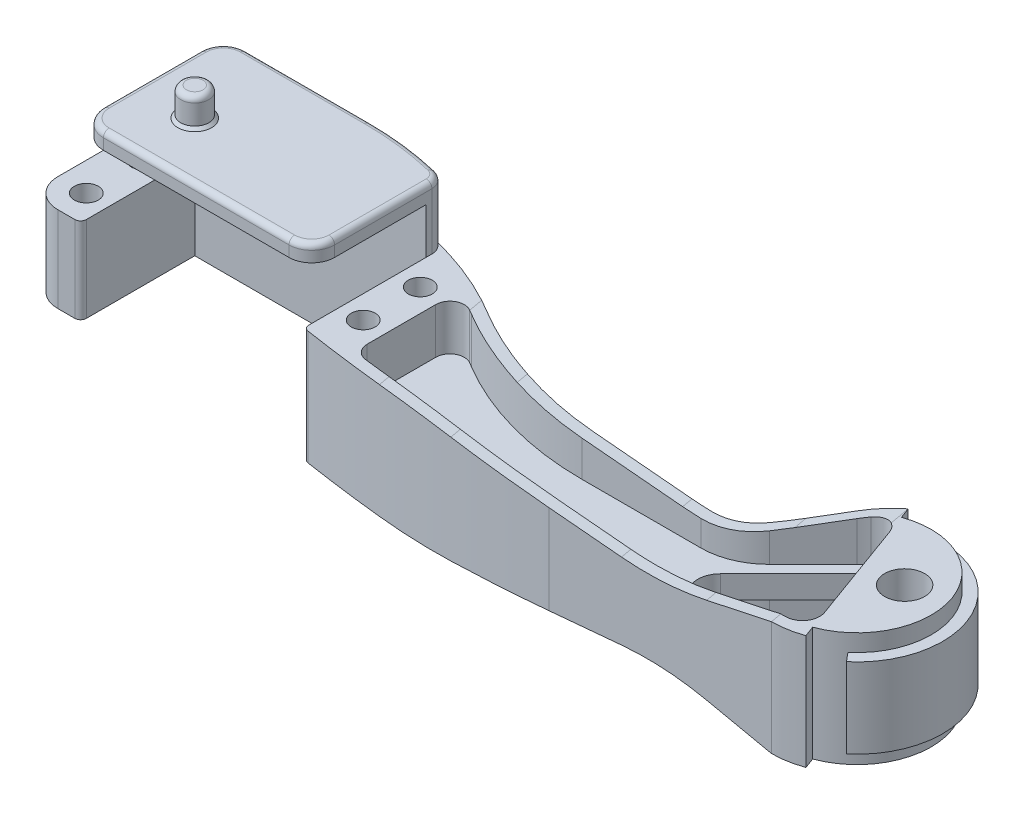
SolidWorks part; units mm, degrees
ref_plane "Alzado" through (0, 0, 0) normal (0, 0, 1) x (1, 0, 0)
ref_plane "Planta" through (0, 0, 0) normal (0, 1, 0) x (1, 0, 0)
ref_plane "Vista lateral" through (0, 0, 0) normal (1, 0, 0) x (0, 0, -1)
sketch "Croquis1" plane through (0, 0, 0) normal (0, 1, 0) x (1, 0, 0)
  line L0 (-65, 15) -> (-40.2965, 15)
  line L1 (-75, -15) -> (75, -15) construction
  line L2 (-75, -15) -> (-75, 15) construction
  line L3 (-75, 15) -> (75, 15) construction
  line L4 (75, -15) -> (75, 15) construction
  line L5 (-75, -15) -> (75, 15) construction
  line L6 (-75, 15) -> (75, -15) construction
  line L7 (13.7868, 0) -> (34.6447, 0)
  line L8 (41.7157, 2.9289) -> (49.3934, 10.6066)
  line L9 (60, -15) -> (21, -15)
  line L10 (-25.5, -10.5178) -> (-25.5, 10)
  line L11 (-25.5, 10) -> (-66, 10)
  line L12 (-66, 10) -> (-66, -9)
  line L13 (-67, -10) -> (-70, -10)
  line L14 (-75, -5) -> (-75, 5)
  line L18 (57.4617, 6.9739) -> (62.5383, -6.9739)
  line L19 (59.7192, -11) -> (43.109, -11)
  line L20 (40.2805, -4.1716) -> (52.5213, 8.0692)
  line L21 (60, 0) -> (60, 15) construction
  line L22 (57.4617, 6.9739) -> (54.8697, 14.0954) construction
  line L23 (62.5383, -6.9739) -> (65.1303, -14.0954) construction
  line L24 (60, 0) -> (69.6418, -11.4907) construction
  line L25 (54.8697, 14.0954) -> (55.5537, 12.216)
  line L26 (60, 15) -> (60, 13)
  line L27 (65.1303, -14.0954) -> (64.4463, -12.216)
  line L28 (69.6418, -11.4907) -> (68.3562, -9.9586)
  line L29 (60, 0) -> (66.108, 2.2231) construction
  arc A0 (-40.2965, 15) -> (-11.9671, 7.1429) centre (-40.2965, -40) cw
  arc A1 (-11.9671, 7.1429) -> (13.7868, 0) centre (13.7868, 50) ccw
  arc A3 (49.3934, 10.6066) -> (54.8697, 14.0954) centre (60, 0) cw
  arc A4 (21, -15) -> (-24.6522, -11.5061) centre (21, 285) cw
  arc A5 (-24.6522, -11.5061) -> (-25.5, -10.5178) centre (-24.5, -10.5178) cw
  arc A6 (-66, -9) -> (-67, -10) centre (-67, -9) cw
  arc A7 (-75, 5) -> (-65, 15) centre (-65, 5) cw
  arc A8 (-75, -5) -> (-70, -10) centre (-70, -5) ccw
  arc A9 (41.7157, 2.9289) -> (34.6447, 0) centre (34.6447, 10) cw
  arc A10 (43.109, -11) -> (40.2805, -4.1716) centre (43.109, -7) cw
  arc A11 (57.4617, 6.9739) -> (52.5213, 8.0692) centre (54.6426, 5.9479) ccw
  arc A12 (62.5383, -6.9739) -> (59.7192, -11) centre (59.7192, -8) cw
  arc A14 (65.1303, -14.0954) -> (60, -15) centre (60, 0) cw
  arc A15 (60, 15) -> (69.6418, -11.4907) centre (60, 0) cw
  arc A16 (64.4463, -12.216) -> (68.3562, -9.9586) centre (60, 0) ccw
  arc A17 (60, 13) -> (55.5537, 12.216) centre (60, 0) ccw
  circle A18 centre (66.108, 2.2231) radius 3.5
  point P0 (0, 0)
  point P33 (-75, -10)
  point P36 (60, 0)
  point P37 (60, 0)
  point P38 (60, 0)
  point P51 (38.7868, 0)
  dimension "D3" = 10
  dimension "D4" = 5
  dimension "D6" = 1
  dimension "D10" = 55
  dimension "D11" = 50
  dimension "D13" = 10
  dimension "D14" = 15
  dimension "D16" = 300
  dimension "D17" = 1
  dimension "D21" = 4
  dimension "D22" = 3
  dimension "D23" = 3
  dimension "D24" = 13
  dimension "D26" = 6.5
  dimension "D27" = 7
  dimension "D1" = 150
  dimension "D2" = 30
  dimension "D5" = 10
  dimension "D7" = 19
  dimension "D8" = 3
  dimension "D9" = 40.5
  dimension "D12" = 25
  dimension "D15" = 39
  dimension "D18" = 135
  dimension "D19" = 20
  dimension "D20" = 4
  dimension "D25" = 20
extrude "Saliente-Extruir1" add sketch "Croquis1" along normal mid plane 4
sketch "Croquis2" plane through (0, 0, 0) normal (0, 1, 0) x (1, 0, 0)
  line L0 (54.8697, 14.0954) -> (55.5537, 12.216) construction
  line L1 (41.7157, 2.9289) -> (49.3934, 10.6066) construction
  line L2 (13.7868, 0) -> (34.6447, 0) construction
  line L3 (60, -15) -> (21, -15) construction
  line L4 (-65, 15) -> (-40.2965, 15) construction
  line L5 (-25.5, -10.5178) -> (-25.5, 10) construction
  line L6 (-25.5, 10) -> (-66, 10) construction
  line L7 (-66, 10) -> (-66, -9) construction
  line L8 (-67, -10) -> (-70, -10) construction
  line L9 (-75, -5) -> (-75, 5) construction
  line L10 (54.8697, 14.0954) -> (55.5537, 12.216)
  line L11 (41.7157, 2.9289) -> (49.3934, 10.6066)
  line L12 (13.7868, 0) -> (34.6447, 0)
  line L13 (60, -15) -> (21, -15)
  line L14 (-65, 15) -> (-40.2965, 15)
  line L15 (-25.5, -10.5178) -> (-25.5, 10)
  line L16 (-25.5, 10) -> (-66, 10)
  line L17 (-66, 10) -> (-66, -9)
  line L18 (-67, -10) -> (-70, -10)
  line L19 (-75, -5) -> (-75, 5)
  line L20 (65.1303, -14.0954) -> (64.4463, -12.216) construction
  line L21 (65.1303, -14.0954) -> (64.4463, -12.216)
  line L22 (13.7868, -2) -> (34.6447, -2)
  line L23 (43.1299, 1.5147) -> (50.8076, 9.1924)
  line L24 (60, -13) -> (21, -13)
  line L25 (-17.5, 3.7074) -> (-17.5, -8.2989)
  line L26 (63.2627, -8.9641) -> (56.7373, 8.9641)
  arc A0 (-25.5, -10.5178) -> (-24.6522, -11.5061) centre (-24.5, -10.5178) ccw construction
  circle A1 centre (66.108, 2.2231) radius 3.5 construction
  arc A2 (54.8697, 14.0954) -> (49.3934, 10.6066) centre (60, 0) ccw construction
  arc A3 (34.6447, 0) -> (41.7157, 2.9289) centre (34.6447, 10) ccw construction
  arc A4 (60, -15) -> (65.1303, -14.0954) centre (60, 0) ccw construction
  arc A5 (-24.6522, -11.5061) -> (21, -15) centre (21, 285) ccw construction
  arc A6 (-11.9671, 7.1429) -> (13.7868, 0) centre (13.7868, 50) ccw construction
  arc A7 (-11.9671, 7.1429) -> (-40.2965, 15) centre (-40.2965, -40) ccw construction
  arc A8 (-67, -10) -> (-66, -9) centre (-67, -9) ccw construction
  arc A9 (-75, -5) -> (-70, -10) centre (-70, -5) ccw construction
  arc A10 (-65, 15) -> (-75, 5) centre (-65, 5) ccw construction
  arc A11 (-25.5, -10.5178) -> (-24.6522, -11.5061) centre (-24.5, -10.5178) ccw
  circle A12 centre (66.108, 2.2231) radius 3.5
  arc A13 (54.8697, 14.0954) -> (49.3934, 10.6066) centre (60, 0) ccw
  arc A14 (34.6447, 0) -> (41.7157, 2.9289) centre (34.6447, 10) ccw
  arc A15 (60, -15) -> (65.1303, -14.0954) centre (60, 0) ccw
  arc A16 (-24.6522, -11.5061) -> (21, -15) centre (21, 285) ccw
  arc A17 (-11.9671, 7.1429) -> (13.7868, 0) centre (13.7868, 50) ccw
  arc A18 (-11.9671, 7.1429) -> (-40.2965, 15) centre (-40.2965, -40) ccw
  arc A19 (-67, -10) -> (-66, -9) centre (-67, -9) ccw
  arc A20 (-75, -5) -> (-70, -10) centre (-70, -5) ccw
  arc A21 (-65, 15) -> (-75, 5) centre (-65, 5) ccw
  arc A22 (64.4463, -12.216) -> (55.5537, 12.216) centre (60, 0) ccw
  arc A23 (-12.9973, 5.4286) -> (-13.7477, 5.8712) centre (-40.2965, -40) ccw
  arc A24 (-12.9973, 5.4286) -> (13.7868, -2) centre (13.7868, 50) ccw
  arc A25 (34.6447, -2) -> (43.1299, 1.5147) centre (34.6447, 10) ccw
  arc A26 (52.0937, 10.3194) -> (50.8076, 9.1924) centre (60, 0) ccw
  arc A27 (-15.3046, -10.7803) -> (21, -13) centre (21, 285) ccw
  arc A28 (60, -13) -> (60.5767, -12.9872) centre (60, 0) ccw
  arc A29 (-12.9973, 5.4286) -> (-40.2965, 13) centre (-40.2965, -40) ccw construction
  arc A30 (-24.3478, -9.5294) -> (21, -13) centre (21, 285) ccw construction
  arc A31 (55.5537, 12.216) -> (50.8076, 9.1924) centre (60, 0) ccw construction
  arc A32 (56.7373, 8.9641) -> (52.0937, 10.3194) centre (53.9183, 7.938) ccw
  arc A33 (60, -13) -> (64.4463, -12.216) centre (60, 0) ccw construction
  arc A34 (63.2627, -8.9641) -> (60.5767, -12.9872) centre (60.4436, -9.9902) cw
  arc A35 (-13.7477, 5.8712) -> (-17.5, 3.7074) centre (-15, 3.7074) ccw
  arc A36 (-17.5, -8.2989) -> (-15.3046, -10.7803) centre (-15, -8.2989) ccw
  dimension "D1" = 2
  dimension "D4" = 3
  dimension "D5" = 3
  dimension "D6" = 2.5
  dimension "D7" = 2.5
  dimension "D3" = 8
  dimension "D2" = 2
extrude "Saliente-Extruir2" add sketch "Croquis2" along normal mid plane 20
sketch "Croquis3" plane through (0, 0, 0) normal (0, 1, 0) x (1, 0, 0)
  line L0 (69.6418, -11.4907) -> (68.3562, -9.9586) construction
  line L1 (60, 15) -> (60, 13) construction
  line L2 (69.6418, -11.4907) -> (68.3562, -9.9586)
  line L3 (60, 15) -> (60, 13)
  arc A0 (69.6418, -11.4907) -> (60, 15) centre (60, 0) ccw construction
  arc A1 (69.6418, -11.4907) -> (60, 15) centre (60, 0) ccw
  arc A2 (68.3562, -9.9586) -> (60, 13) centre (60, 0) ccw
extrude "Saliente-Extruir3" add sketch "Croquis3" along normal mid plane 14
sketch "Croquis4" plane through (0, 0, 15) normal (0, 0, 1) x (1, 0, 0)
  line L1 (60, 10) -> (60, -10) construction
  line L2 (60, 10) -> (-10, 10)
  line L3 (60, 10) -> (60, -10) construction
  line L4 (60, 10) -> (48.6517, 7.5772)
  line L5 (33.7402, 6.6757) -> (3.4163, 9.3988)
  line L6 (16.5, 0) -> (-16.5, 0) construction
  line L7 (60, -10) -> (-10, -10)
  line L8 (33.7402, -6.6757) -> (3.4163, -9.3988)
  line L9 (60, -10) -> (48.6517, -7.5772)
  arc A1 (3.4163, 9.3988) -> (-10, 10) centre (-10, -140) ccw
  arc A2 (48.6517, 7.5772) -> (33.7402, 6.6757) centre (38.2123, 56.4753) cw
  arc A3 (3.4163, -9.3988) -> (-10, -10) centre (-10, 140) cw
  arc A4 (48.6517, -7.5772) -> (33.7402, -6.6757) centre (38.2123, -56.4753) ccw
  point P12 (41.264, 6)
  dimension "D2" = 6
  dimension "D3" = 150
  dimension "D5" = 50
  dimension "D1" = 70
  dimension "D4" = 38
sketch "Croquis5" plane through (0, 0, 0) normal (0, 1, 0) x (1, 0, 0)
  line L0 (60, -15) -> (54.8697, 14.0954) construction
  arc A0 (60, -15) -> (65.1303, -14.0954) centre (60, 0) ccw construction
  arc A1 (54.8697, 14.0954) -> (49.3934, 10.6066) centre (60, 0) ccw construction
  arc A2 (60, -15) -> (65.1303, -14.0954) centre (60, 0) ccw
  arc A3 (54.8697, 14.0954) -> (49.3934, 10.6066) centre (60, 0) ccw
extrude "Cortar-Extruir1" cut sketch "Croquis4" along direction (-0.1736, 0, -0.9848) on the side against the normal through all
sketch "Croquis7" plane through (0, 10, 0) normal (0, 1, 0) x (1, 0, 0)
  line L0 (-70, -10) -> (-67, -10) construction
  line L1 (-75, 5) -> (-75, -5) construction
  line L2 (-70, -10) -> (-67, -10)
  line L3 (-75, 5) -> (-75, -5)
  line L6 (-65, 15) -> (-62, 15)
  line L7 (-66, -9) -> (-66, 11)
  arc A0 (-67, -10) -> (-66, -9) centre (-67, -9) ccw construction
  arc A1 (-75, -5) -> (-70, -10) centre (-70, -5) ccw construction
  arc A3 (-67, -10) -> (-66, -9) centre (-67, -9) ccw
  arc A4 (-75, -5) -> (-70, -10) centre (-70, -5) ccw
  arc A6 (-65, 15) -> (-75, 5) centre (-65, 5) ccw construction
  arc A7 (-65, 15) -> (-75, 5) centre (-65, 5) ccw
  arc A8 (-62, 15) -> (-66, 11) centre (-62, 11) ccw
  dimension "D1" = 4
extrude "Cortar-Extruir3" cut sketch "Croquis7" against normal blind 5
sketch "Croquis8" plane through (0, 10, 0) normal (0, 1, 0) x (1, 0, 0)
  line L7 (-40.2965, 15) -> (-62, 15) construction
  line L8 (-66, 10) -> (-66, 11) construction
  line L11 (-66, 10) -> (-25.5, 10) construction
  line L12 (-40.2965, 15) -> (-62, 15)
  line L13 (-66, 10) -> (-66, 11)
  line L14 (-66, 10) -> (-25.5, 10)
  line L15 (-25.5, 10) -> (-25.5, 11.0397)
  arc A6 (-14.1211, 8.372) -> (-40.2965, 15) centre (-40.2965, -40) ccw construction
  arc A7 (-62, 15) -> (-66, 11) centre (-62, 11) ccw construction
  arc A8 (-27.4145, 13.4701) -> (-40.2965, 15) centre (-40.2965, -40) ccw
  arc A9 (-62, 15) -> (-66, 11) centre (-62, 11) ccw
  arc A10 (-25.5, 11.0397) -> (-27.4145, 13.4701) centre (-28, 11.0397) ccw
  dimension "D1" = 2.5
extrude "Saliente-Extruir4" add sketch "Croquis8" along normal blind 8
sketch "Croquis9" plane through (0, 18, 0) normal (0, 1, 0) x (1, 0, 0)
  line L0 (-40.2965, 15) -> (-62, 15) construction
  line L1 (-40.2965, 15) -> (-62, 15)
  line L2 (-66, 11) -> (-66, -6)
  line L3 (-62, -10) -> (-29.5, -10)
  line L4 (-25.5, -6) -> (-25.5, 11.0397)
  line L5 (-70, -10) -> (-67, -10) construction
  line L6 (-70, -10) -> (-67, -10) construction
  arc A0 (-25.5, 11.0397) -> (-27.4145, 13.4701) centre (-28, 11.0397) ccw construction
  arc A1 (-27.4145, 13.4701) -> (-40.2965, 15) centre (-40.2965, -40) ccw construction
  arc A2 (-62, 15) -> (-66, 11) centre (-62, 11) ccw construction
  arc A3 (-25.5, 11.0397) -> (-27.4145, 13.4701) centre (-28, 11.0397) ccw
  arc A4 (-27.4145, 13.4701) -> (-40.2965, 15) centre (-40.2965, -40) ccw
  arc A5 (-62, 15) -> (-66, 11) centre (-62, 11) ccw
  arc A6 (-25.5, -6) -> (-29.5, -10) centre (-29.5, -6) cw
  arc A7 (-62, -10) -> (-66, -6) centre (-62, -6) cw
  dimension "D1" = 4
extrude "Saliente-Extruir5" add sketch "Croquis9" along normal blind 2.9
sketch "Croquis10" plane through (0, -10, 0) normal (0, -1, 0) x (1, 0, 0)
  line L0 (-45.75, -10) -> (-45.75, -15) construction
  line L1 (-66, -10) -> (-25.5, -10) construction
  line L2 (-40.2965, -15) -> (-65, -15) construction
  circle A1 centre (-70, -5) radius 2.1
  circle A2 centre (-70, 5) radius 2.1
  circle A3 centre (-21.5, -5) radius 2.1
  circle A4 centre (-21.5, 5) radius 2.1
  dimension "D1" = 10
  dimension "D3" = 4.2
  dimension "D2" = 10
  dimension "D4" = 4
extrude "Cortar-Extruir4" cut sketch "Croquis10" against normal through all
sketch "Croquis11" plane through (0, 20.9, 0) normal (0, 1, 0) x (1, 0, 0)
  line L0 (-66, 11) -> (-66, -6) construction
  line L1 (-62, -10) -> (-29.5, -10) construction
  circle A0 centre (-56, 0) radius 2.45
  dimension "D1" = 10
  dimension "D2" = 4.9
  dimension "D3" = 10
extrude "Saliente-Extruir6" add sketch "Croquis11" along normal blind 5
fillet "Redondeo1" radius 1 1 edges at (-56, 25.9, 2.45)
chamfer "Chaflán1" distance 0.5 angle 45 1 edges at (-56, 20.9, 2.45)
fillet "Redondeo2" radius 1 9 edges at (-64.8284, 20.9, 8.8284) (-66, 20.9, -2.5) (-64.8284, 20.9, -13.8284) (-51.1482, 20.9, -15) (-33.8102, 20.9, -14.6162) (-26.0361, 20.9, -12.5866) (-25.5, 20.9, -2.5198) (-26.6716, 20.9, 8.8284) (-45.75, 20.9, 10)
